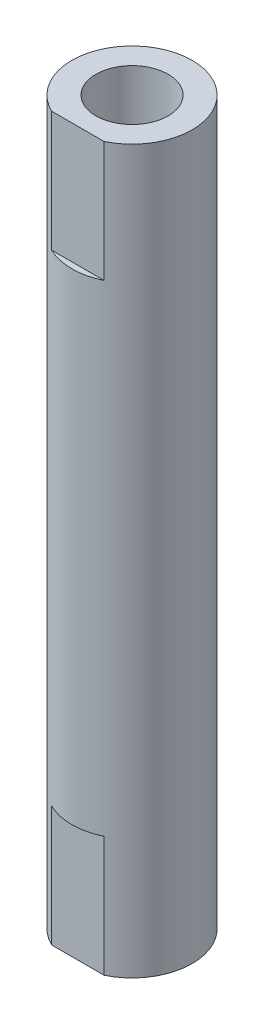
SolidWorks part; units mm, degrees
ref_plane "Front Plane" through (0, 0, 0) normal (0, 0, 1) x (1, 0, 0)
ref_plane "Top Plane" through (0, 0, 0) normal (0, 1, 0) x (1, 0, 0)
ref_plane "Right Plane" through (0, 0, 0) normal (1, 0, 0) x (0, 0, -1)
sketch "Sketch1" plane through (0, 0, 0) normal (0, 1, 0) x (1, 0, 0)
  circle A0 centre (0, 0) radius 5
  circle A1 centre (0, 0) radius 3
  dimension "D1" = 10
  dimension "D2" = 6
extrude "Boss-Extrude1" add sketch "Sketch1" along normal mid plane 60
sketch "Sketch2" plane through (0, -30, 0) normal (0, -1, 0) x (1, 0, 0)
  line L0 (-2.1794, 4.5) -> (2.1794, 4.5)
  circle A0 centre (0, 0) radius 5 construction
  arc A1 (2.1794, 4.5) -> (-2.1794, 4.5) centre (0, 0) ccw
  dimension "D1" = 4.5
extrude "Cut-Extrude1" cut sketch "Sketch2" against normal blind 10
mirror "Mirror1" about plane through (0, 0, 0) normal (0, 1, 0) of "Cut-Extrude1"
